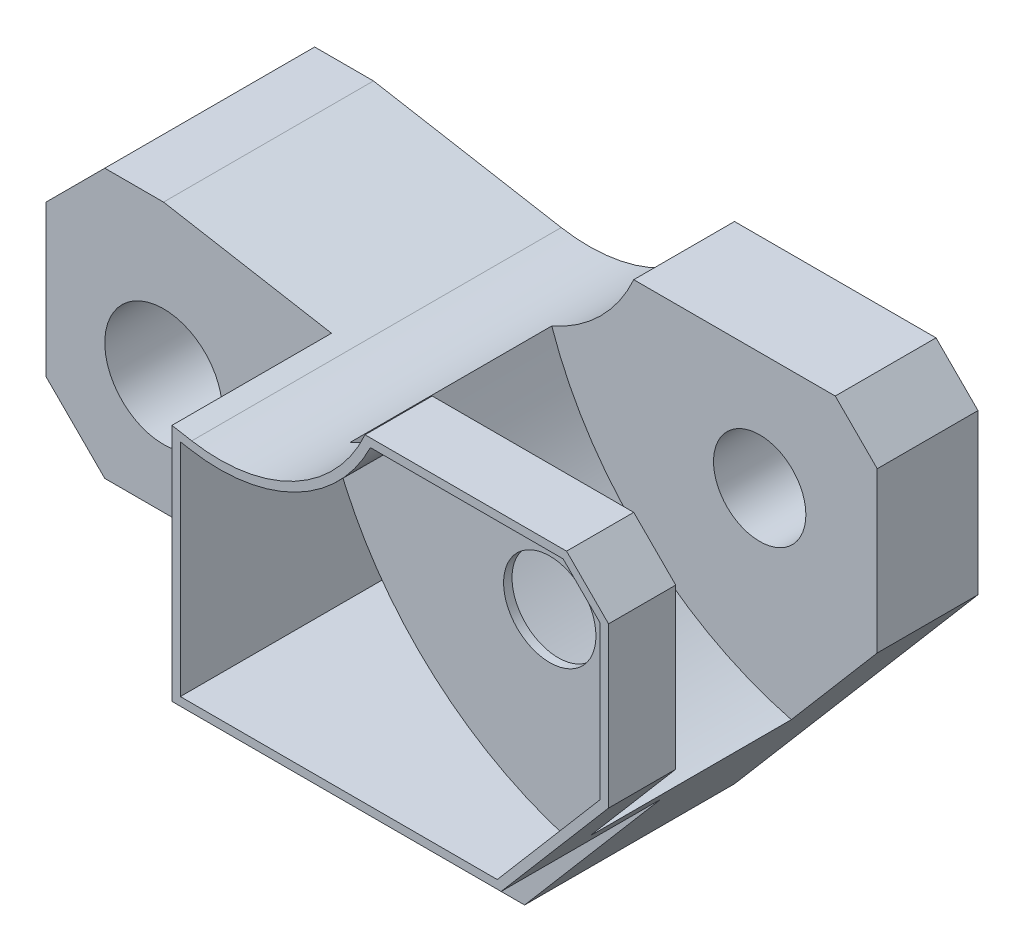
SolidWorks part; units mm, degrees
material "AISI 1020"
ref_plane "Front" through (0, 0, 0) normal (0, 0, 1) x (1, 0, 0)
ref_plane "Top" through (0, 0, 0) normal (0, 1, 0) x (1, 0, 0)
ref_plane "Right" through (0, 0, 0) normal (1, 0, 0) x (0, 0, -1)
sketch "Sketch1" plane through (0, 0, 0) normal (0, 0, 1) x (1, 0, 0)
  line L0 (0, 0) -> (32.5755, 0)
  line L1 (44.297, -19) -> (50, -19)
  line L2 (50, -19) -> (79, 15)
  line L3 (79, 15) -> (79, 34)
  line L4 (79, 34) -> (74, 39)
  line L5 (74, 39) -> (50, 39)
  line L6 (0, 0) -> (-7, 7)
  line L7 (-7, 7) -> (-7, 25)
  line L8 (-7, 25) -> (0, 32)
  line L9 (0, 32) -> (7, 32)
  line L10 (7, 32) -> (29.3614, 28.0571)
  circle A0 centre (7, 14) radius 7
  arc A1 (29.3614, 28.0571) -> (50, 39) centre (32.6607, 46.7684) ccw
  arc A2 (32.5755, 0) -> (37.5212, -4.2647) centre (32.5755, -5) cw
  arc A3 (37.5212, -4.2647) -> (44.297, -19) centre (66.2059, 0) ccw
  point P14 (16.2878, 0)
  dimension "D12" = 14
  dimension "D19" = 19
  dimension "D20" = 5
  dimension "D21" = 29
  dimension "D2" = 5
  dimension "D3" = 24
  dimension "D4" = 29
  dimension "D5" = 45
  dimension "D6" = 45
  dimension "D7" = 45
  dimension "D8" = 7
  dimension "D9" = 7
  dimension "D10" = 14
  dimension "D11" = 14
  dimension "D13" = 14
  dimension "D14" = 32
  dimension "D15" = 10
  dimension "D16" = 58
  dimension "D17" = 86
  dimension "D18" = 19
  dimension "D22" = 29
  dimension "D23" = 19
extrude "Boss-Extrude1" add sketch "Sketch1" against normal blind 44
sketch "Sketch2" plane through (0, 0, 0) normal (0, 0, 1) x (1, 0, 0)
  line L0 (79, 15) -> (79, 34) construction
  line L1 (74, 39) -> (50, 39) construction
  circle A0 centre (65, 25) radius 5.5
  dimension "D3" = 11
  dimension "D1" = 14
  dimension "D2" = 14
extrude "Cut-Extrude1" cut sketch "Sketch2" against normal through all
sketch "Sketch3" plane through (0, 0, 0) normal (0, 0, 1) x (1, 0, 0)
  line L0 (27, 28.4735) -> (27, 0)
  line L1 (29.3614, 28.0571) -> (7, 32) construction
  line L2 (0, 0) -> (32.5755, 0) construction
  line L3 (79, 15) -> (79, 34) construction
  dimension "D1" = 52
extrude "Cut-Extrude2" cut sketch "Sketch3" against normal blind 19 and the other way through all flip side to cut
sketch "Sketch4" plane through (0, 0, 0) normal (0, 0, 1) x (1, 0, 0)
  line L0 (32.5755, 0) -> (66.2059, 0)
  line L1 (50, -19) -> (79, 15) construction
extrude "Cut-Extrude3" cut sketch "Sketch4" against normal blind 19 and the other way through all flip side to cut
sketch "Sketch5" plane through (0, 0, 0) normal (0, 0, 1) x (1, 0, 0)
  line L0 (66.2059, 0) -> (79, 15) construction
  line L1 (74, 39) -> (50, 39) construction
  line L2 (79, 15) -> (79, 34) construction
  arc A0 (40.2369, 29.3443) -> (68.7647, 3) centre (79, 42.7019) ccw
  arc A1 (29.3614, 28.0571) -> (50, 39) centre (32.6607, 46.7684) ccw construction
  dimension "D1" = 41
  dimension "D2" = 36
ref_plane "Plane1" through (0, 0, -8) normal (0, 0, 1) x (1, 0, 0)
curve "Curve1"
sketch "Sketch7" plane through (0, 0, -8) normal (0, 0, 1) x (1, 0, 0)
  line L0 (66.2059, 0) -> (79, 15) construction
  line L1 (79, 34) -> (74, 39) construction
  line L2 (74, 39) -> (50, 39) construction
  line L3 (79, 15) -> (79, 34) construction
  line L4 (68.7647, 3) -> (79, 15)
  line L5 (79, 15) -> (79, 34)
  line L6 (79, 34) -> (74, 39)
  line L7 (74, 39) -> (50, 39)
  arc A0 (40.2369, 29.3443) -> (68.7647, 3) centre (79, 42.7019) ccw
  arc A1 (40.2369, 29.3443) -> (68.7647, 3) centre (79, 42.7019) ccw construction
  arc A2 (29.3614, 28.0571) -> (50, 39) centre (32.6607, 46.7684) ccw construction
  arc A4 (40.2369, 29.3443) -> (50, 39) centre (32.6607, 46.7684) ccw
  dimension "D1" = 41
extrude "Cut-Extrude5" cut sketch "Sketch7" against normal blind 24
shell "Shell1" [suppressed] thickness 1
sketch "Sketch8" plane through (0, 0, 0) normal (0, 0, 1) x (1, 0, 0)
  line L14 (28, 1) -> (65.7445, 1)
  line L15 (65.7445, 1) -> (78, 15.3685)
  line L16 (78, 15.3685) -> (78, 33.5858)
  line L17 (78, 33.5858) -> (73.5858, 38)
  line L18 (73.5858, 38) -> (50.6361, 38)
  line L19 (29.1877, 27.0723) -> (28, 27.2817)
  line L20 (28, 27.2817) -> (28, 1)
  line L21 (28, 1) -> (65.7445, 1)
  line L22 (65.7445, 1) -> (78, 15.3685)
  line L23 (78, 15.3685) -> (78, 33.5858)
  line L24 (78, 33.5858) -> (73.5858, 38)
  line L25 (73.5858, 38) -> (50.6361, 38)
  line L26 (29.1877, 27.0723) -> (28, 27.2817)
  line L27 (28, 27.2817) -> (28, 1)
  arc A2 (29.1877, 27.0723) -> (50.6361, 38) centre (32.6607, 46.7684) ccw
  arc A3 (29.1877, 27.0723) -> (50.6361, 38) centre (32.6607, 46.7684) ccw
  dimension "D1" = 1
extrude "Cut-Extrude6" cut sketch "Sketch8" against normal blind 7
sketch "Sketch9" plane through (0, 0, -7) normal (0, 0, 1) x (1, 0, 0)
  arc A4 (39.2915, 29.0185) -> (68.5151, 2.0317) centre (79, 42.7019) ccw
  arc A5 (40.2369, 29.3443) -> (68.7647, 3) centre (79, 42.7019) ccw construction
  arc A6 (40.2369, 29.3443) -> (68.7647, 3) centre (79, 42.7019) ccw
  point P3 (39.3708, 27.9277)
  point P4 (67.0682, 2.552)
  point P7 (0, 0)
  point P8 (39.7511, 28.0674)
  dimension "D1" = 1
extrude "Cut-Extrude7" cut sketch "Sketch9" against normal blind 25
